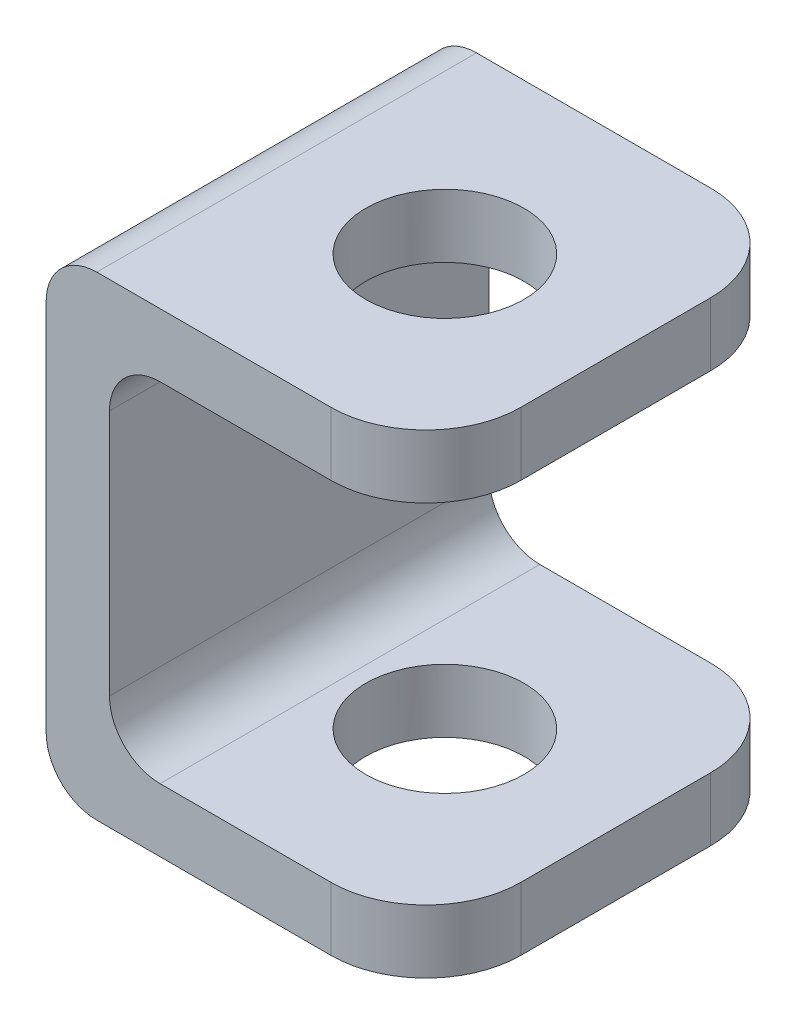
SolidWorks part; units mm, degrees
ref_plane "Front Plane" through (0, 0, 0) normal (0, 0, 1) x (1, 0, 0)
ref_plane "Top Plane" through (0, 0, 0) normal (0, 1, 0) x (1, 0, 0)
ref_plane "Right Plane" through (0, 0, 0) normal (1, 0, 0) x (0, 0, -1)
sketch "Sketch1" plane through (0, 0, 0) normal (0, 0, 1) x (1, 0, 0)
  line L0 (0, -37.5) -> (0, 37.5)
  line L1 (0, 37.5) -> (60, 37.5)
  line L2 (60, 37.5) -> (60, 27.5)
  line L3 (60, 27.5) -> (10, 27.5)
  line L4 (10, 27.5) -> (10, -27.5)
  line L5 (-25.1069, 0) -> (68.6489, 0) construction
  line L6 (60, -37.5) -> (60, -27.5)
  line L7 (60, -27.5) -> (10, -27.5)
  line L8 (0, -37.5) -> (60, -37.5)
  point P12 (10, 0)
  point P13 (0, 0)
  dimension "D1" = 37.5
  dimension "D2" = 60
  dimension "D3" = 10
  dimension "D4" = 10
extrude "Boss-Extrude1" add sketch "Sketch1" along normal blind 60
fillet "Fillet1" radius 15 4 edges at (60, -32.5, 60) (60, -32.5, 0) (60, 32.5, 0) (60, 32.5, 60)
fillet "Fillet2" radius 8 4 edges at (10, 27.5, 30) (10, -27.5, 30) (0, -37.5, 30) (0, 37.5, 30)
sketch "Sketch2" plane through (0, 37.5, 0) normal (0, 1, 0) x (1, 0, 0)
  line L0 (8, 0) -> (8, -60) construction
  circle A0 centre (33, -30) radius 12.5
  point P0 (33, -30)
  dimension "D1" = 25
  dimension "D2" = 25
extrude "Cut-Extrude1" cut sketch "Sketch2" against normal blind 100
sketch "Sketch4" plane through (0, 0, 0) normal (-1, 0, 0) x (0, 0, 1)
  line L4 (17.3, 12.7) -> (42.7, 12.7)
  line L5 (17.3, 12.7) -> (17.3, -12.7)
  line L6 (17.3, -12.7) -> (42.7, -12.7)
  line L7 (42.7, 12.7) -> (42.7, -12.7)
  line L8 (17.3, 12.7) -> (42.7, -12.7) construction
  line L9 (17.3, -12.7) -> (42.7, 12.7) construction
  point P2 (30, 0)
  dimension "D1" = 25.4
  dimension "D2" = 25.4
extrude "Cut-Extrude2" cut sketch "Sketch4" against normal blind 0.1
